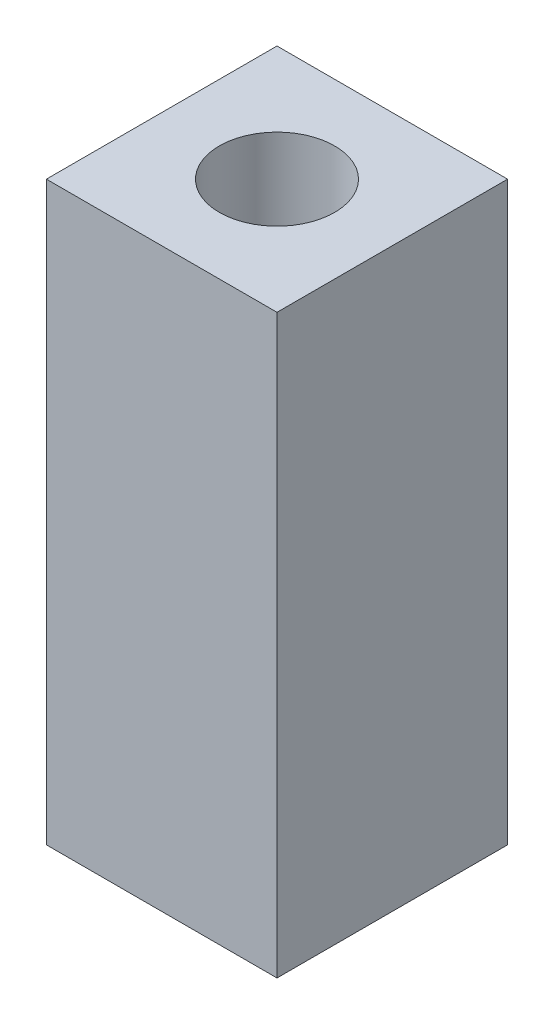
SolidWorks part; units mm, degrees
ref_plane "前视基准面" through (0, 0, 0) normal (0, 0, 1) x (1, 0, 0)
ref_plane "上视基准面" through (0, 0, 0) normal (0, 1, 0) x (1, 0, 0)
ref_plane "右视基准面" through (0, 0, 0) normal (1, 0, 0) x (0, 0, -1)
other "Configuration Table"
sketch "Sketch1" plane through (0, 0, 0) normal (0, 1, 0) x (1, 0, 0)
  line L1 (0, 0) -> (6, 0)
  line L2 (0, 0) -> (0, -6)
  line L3 (0, -6) -> (6, -6)
  line L4 (6, 0) -> (6, -6)
  dimension "D1" = 6
  dimension "D2" = 6
extrude "Boss-Extrude1" add sketch "Sketch1" along normal blind 15
sketch "Sketch2" plane through (0, 15, 0) normal (0, 1, 0) x (1, 0, 0)
  line L0 (6, -3) -> (0, -3) construction
  line L1 (6, -6) -> (6, 0) construction
  line L2 (0, 0) -> (0, -6) construction
  circle A0 centre (3, -3) radius 1.5
  dimension "D1" = 3
extrude "Cut-Extrude1" cut sketch "Sketch2" against normal through all
